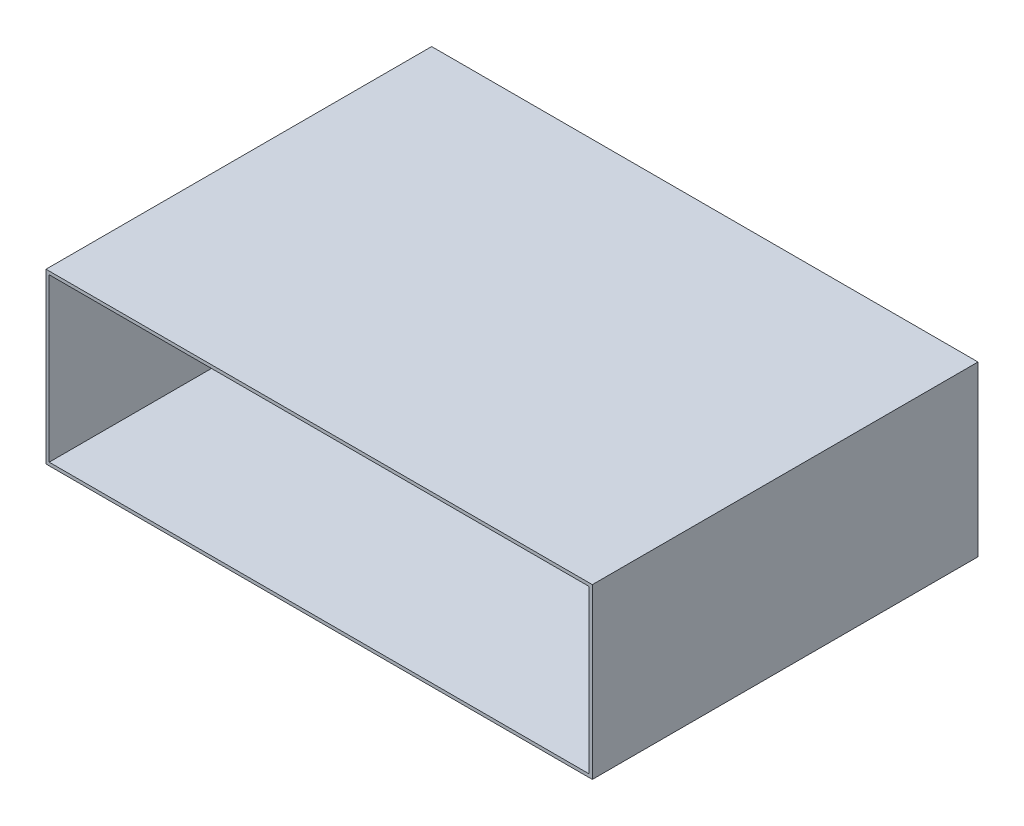
SolidWorks part; units mm, degrees
ref_plane "Front Plane" through (0, 0, 0) normal (0, 0, 1) x (1, 0, 0)
ref_plane "Top Plane" through (0, 0, 0) normal (0, 1, 0) x (1, 0, 0)
ref_plane "Right Plane" through (0, 0, 0) normal (1, 0, 0) x (0, 0, -1)
sketch "Sketch1" plane through (0, 0, 0) normal (0, 1, 0) x (1, 0, 0)
  line L1 (-215.9, 152.4) -> (215.9, 152.4)
  line L2 (-215.9, 152.4) -> (-215.9, -152.4)
  line L3 (-215.9, -152.4) -> (215.9, -152.4)
  line L4 (215.9, 152.4) -> (215.9, -152.4)
  line L5 (-215.9, 152.4) -> (215.9, -152.4) construction
  line L6 (-215.9, -152.4) -> (215.9, 152.4) construction
  point P0 (0, 0)
  dimension "D1" = 304.8
  dimension "D2" = 431.8
extrude "Boss-Extrude1" add sketch "Sketch1" along normal blind 133.35
sketch "Sketch2" plane through (0, 0, 0) normal (0, 1, 0) x (1, 0, 0)
  line L0 (-215.9, 152.4) -> (-215.9, -152.4) construction
  line L1 (213.36, -152.4) -> (-213.36, -152.4)
  line L2 (213.36, -152.4) -> (213.36, 149.86)
  line L3 (213.36, 149.86) -> (-213.36, 149.86)
  line L4 (-213.36, -152.4) -> (-213.36, 149.86)
  line L5 (213.36, -152.4) -> (-213.36, 149.86) construction
  line L6 (213.36, 149.86) -> (-213.36, -152.4) construction
  line L7 (215.9, 152.4) -> (-215.9, 152.4) construction
  line L8 (-215.9, -152.4) -> (215.9, -152.4) construction
  line L9 (215.9, -152.4) -> (215.9, 152.4) construction
  point P0 (0, 0)
  dimension "D1" = 2.54
  dimension "D2" = 2.54
  dimension "D3" = 0
  dimension "D4" = 2.54
extrude "Cut-Extrude1" cut sketch "Sketch2" along normal blind 128.27 from offset 2.54
